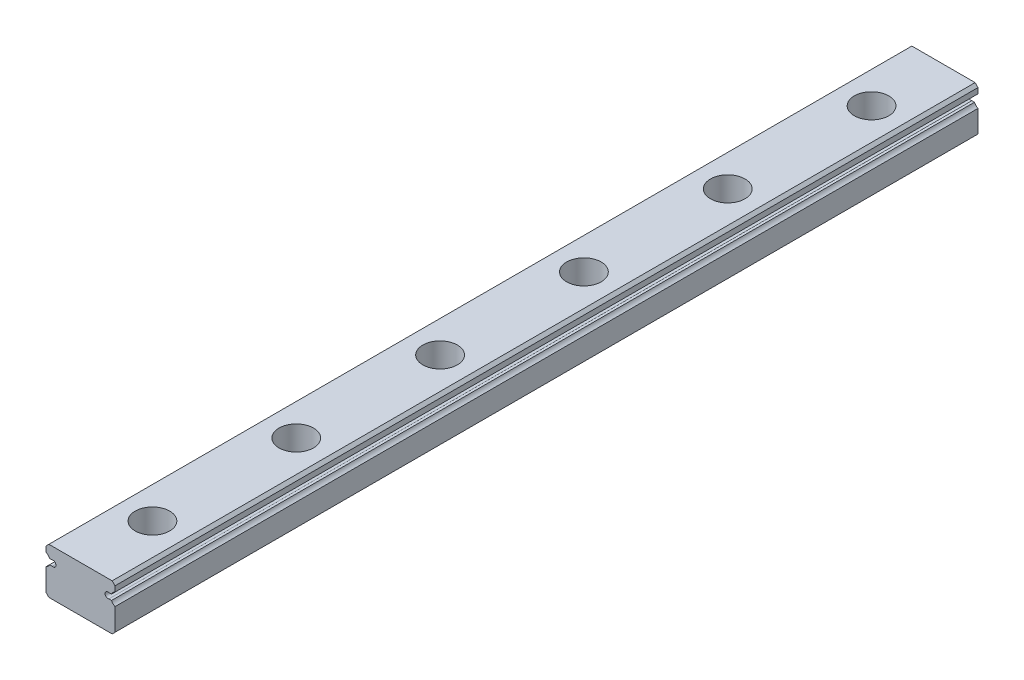
SolidWorks part; units mm, degrees
material "Chrome Stainless Steel"
ref_plane "Front Plane" through (0, 0, 0) normal (0, 0, 1) x (1, 0, 0)
ref_plane "Top Plane" through (0, 0, 0) normal (0, 1, 0) x (1, 0, 0)
ref_plane "Right Plane" through (0, 0, 0) normal (1, 0, 0) x (0, 0, -1)
sketch "Sketch1" plane through (0, 0, 0) normal (0, 0, 1) x (1, 0, 0)
  line L0 (0, 4) -> (0, -4) construction
  line L1 (5.5, -4) -> (-5.5, -4)
  line L2 (-5.5, -4) -> (-6, -3.5)
  line L3 (-6, -3.5) -> (-6, 0.3689)
  line L4 (5.5, 4) -> (-5.5, 4)
  line L5 (-5.5, 4) -> (-6, 3.5)
  line L6 (-6, 2.5511) -> (-6, 3.5)
  line L7 (-5.3839, 0.985) -> (-4.9211, 0.985)
  line L8 (-5.3839, 1.935) -> (-4.9211, 1.935)
  line L9 (5.3839, 0.985) -> (4.9211, 0.985)
  line L10 (5.5, 4) -> (6, 3.5)
  line L11 (6, 2.5511) -> (6, 3.5)
  line L12 (5.3839, 1.935) -> (4.9211, 1.935)
  line L13 (6, -3.5) -> (6, 0.3689)
  line L14 (5.5, -4) -> (6, -3.5)
  circle A0 centre (-6.475, 1.46) radius 1.19 construction
  circle A1 centre (-4.765, 1.46) radius 0.5 construction
  arc A2 (-6, 0.3689) -> (-5.3839, 0.985) centre (-6.475, 1.46) ccw
  arc A3 (-5.3839, 1.935) -> (-6, 2.5511) centre (-6.475, 1.46) ccw
  arc A4 (-4.9211, 0.985) -> (-4.9211, 1.935) centre (-4.765, 1.46) ccw
  arc A5 (5.3839, 1.935) -> (6, 2.5511) centre (6.475, 1.46) cw
  arc A6 (4.9211, 0.985) -> (4.9211, 1.935) centre (4.765, 1.46) cw
  arc A7 (6, 0.3689) -> (5.3839, 0.985) centre (6.475, 1.46) cw
  point P4 (0, 0)
  dimension "D5" = 5.46
  dimension "D6" = 6.475
  dimension "D7" = 2.38
  dimension "D11" = 1
  dimension "D12" = 5.46
  dimension "D13" = 4.765
  dimension "D1" = 8
  dimension "D2" = 0.5
  dimension "D3" = 0.5
  dimension "D4" = 6
  dimension "D8" = 0.5
  dimension "D9" = 0.5
  dimension "D10" = 6
  dimension "D14" = 0.475
  dimension "D15" = 0.475
extrude "Boss-Extrude1" add sketch "Sketch1" along normal blind 150 contours L13 A7 L9 A6 L12 A5 L11 L10 L4 L5 L6 A3 L8 A4 L7 A2 L3 L2 L1 L14
sketch "Sketch2" plane through (0, 4, 0) normal (0, 1, 0) x (1, 0, 0)
  line L0 (5.5, 0) -> (-5.5, 0) construction
  circle A0 centre (0, -12.5) radius 3
  dimension "D1" = 12.5
extrude "Cut-Extrude1" cut sketch "Sketch2" against normal blind 4.5
sketch "Sketch3" plane through (0, -0.5, 0) normal (0, 1, 0) x (1, 0, 0)
  circle A0 centre (0, -12.5) radius 1.75
extrude "Cut-Extrude2" cut sketch "Sketch3" against normal through all
pattern_linear "LPattern1" count 6 spacing 25 along (0, 0, 1) of "Cut-Extrude1", "Cut-Extrude2"
